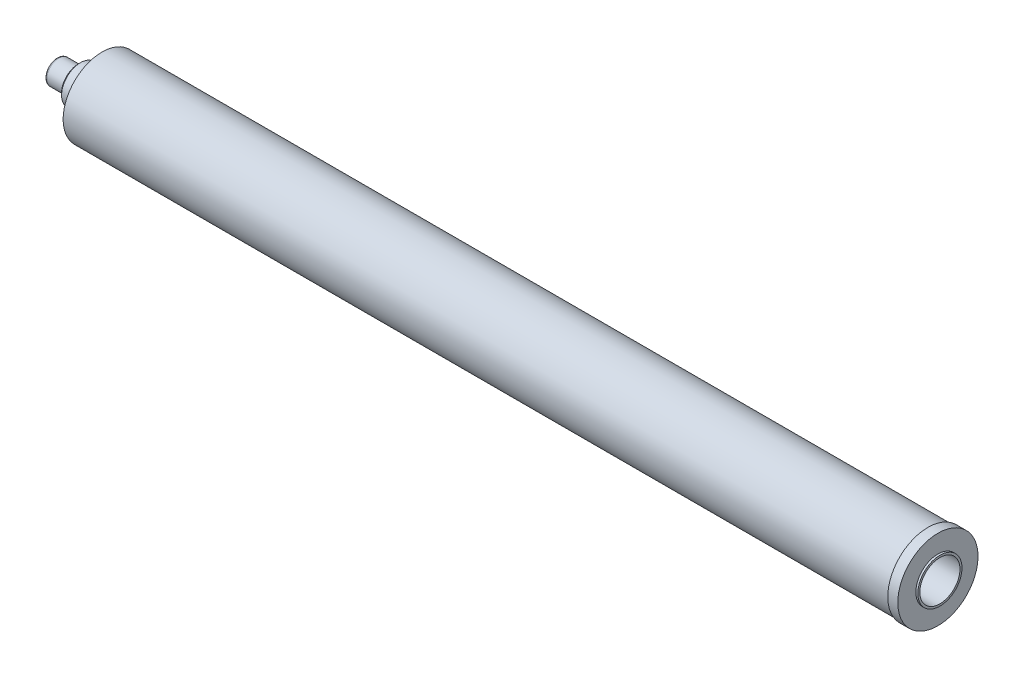
SolidWorks part; units mm, degrees
material "6061 Alloy"
ref_plane "Front Plane" through (0, 0, 0) normal (0, 0, 1) x (1, 0, 0)
ref_plane "Top Plane" through (0, 0, 0) normal (0, 1, 0) x (1, 0, 0)
ref_plane "Right Plane" through (0, 0, 0) normal (1, 0, 0) x (0, 0, -1)
sketch "Sketch1" plane through (0, 0, 0) normal (0, 0, 1) x (1, 0, 0)
  line L0 (0, 0) -> (0, 15.24)
  line L1 (0, 15.24) -> (27.305, 15.24)
  line L2 (27.305, 15.24) -> (27.305, 23.876)
  line L3 (27.305, 23.876) -> (57.15, 23.876)
  line L4 (57.15, 23.876) -> (57.15, 49.2125)
  line L5 (57.15, 49.2125) -> (1103.122, 49.2125)
  line L6 (1103.122, 49.2125) -> (1103.122, 50.8)
  line L7 (1103.122, 50.8) -> (1115.822, 50.8)
  line L8 (1115.822, 50.8) -> (1115.822, 0)
  line L9 (1115.822, 0) -> (0, 0)
  dimension "D1" = 12.7
  dimension "D2" = 50.8
  dimension "D3" = 49.2125
  dimension "D4" = 23.876
  dimension "D5" = 29.845
  dimension "D6" = 57.15
  dimension "D7" = 15.24
  dimension "D8" = 1045.972
revolve "Revolve1" add sketch "Sketch1" angle 360 about L9
hole_wizard "CSK for 3/8 Flat Head Machine Screw (100)1" positions "Sketch2" profile "Sketch3" countersink size "3/8" standard "ANSI Inch"
sketch "Sketch2" plane through (0, 0, 0) normal (-1, 0, 0) x (0, 0, 1)
  point P0 (0, 0)
sketch "Sketch3" plane through (0, 0, 0) normal (0, 1, 0) x (0, 0, 1)
  line L0 (0, 0) -> (0, 28.4295)
  line L1 (0, 28.4295) -> (5.0419, 25.4)
  line L2 (5.0419, 25.4) -> (5.0419, 3.8896)
  line L3 (5.0419, 3.8896) -> (9.6774, 0)
  line L5 (9.6774, 0) -> (0, 0)
  line L6 (-5.0419, 3.8896) -> (-9.6774, 0) construction
  line L10 (0, 28.4295) -> (-5.0419, 25.4) construction
  line L11 (0, -6.35) -> (0, 107.95) construction
  dimension "Hole Dia." = 10.0838
  dimension "Hole Depth" = 25.4
  dimension "Near C'Sink Dia." = 19.3548
  dimension "Near C'Sink Angle" = 100
  dimension "Drill Angle" = 118
fillet "Fillet1" radius 2.54 1 edges at (0, 15.24, 0)
chamfer "Chamfer1" distance 2.54 angle 45 1 edges at (27.305, 23.876, 0)
sketch "Sketch4" plane through (1115.822, 0, 0) normal (1, 0, 0) x (0, 0, -1)
  circle A0 centre (0, 0) radius 25.4
  circle A1 centre (0, 0) radius 27.94
  dimension "D1" = 50.8
  dimension "D2" = 55.88
extrude "Boss-Extrude1" add sketch "Sketch4" along normal blind 2.54
sketch "Sketch5" plane through (1118.362, 0, 0) normal (1, 0, 0) x (0, 0, -1)
  circle A0 centre (0, 0) radius 25.4 construction
  circle A1 centre (0, 0) radius 25.4
extrude "Cut-Extrude1" cut sketch "Sketch5" against normal blind 508
